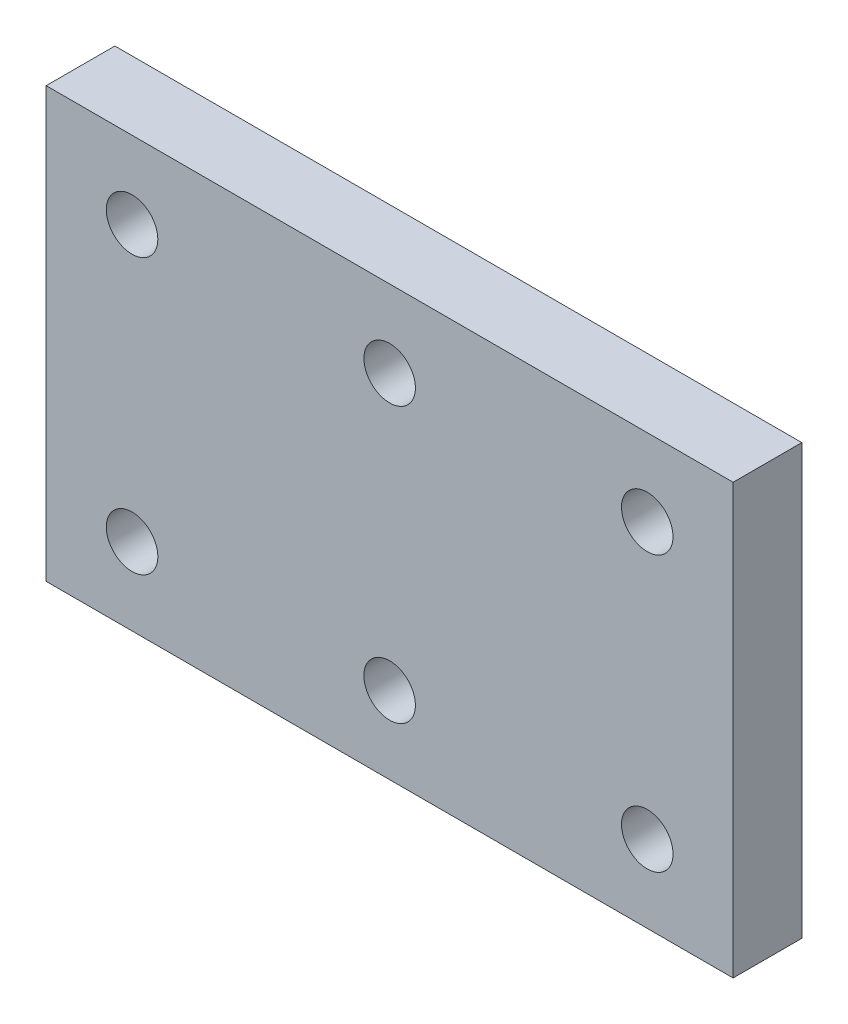
SolidWorks part; units mm, degrees
ref_plane "前视基准面" through (0, 0, 0) normal (0, 0, 1) x (1, 0, 0)
ref_plane "上视基准面" through (0, 0, 0) normal (0, 1, 0) x (1, 0, 0)
ref_plane "右视基准面" through (0, 0, 0) normal (1, 0, 0) x (0, 0, -1)
sketch "草图2" plane through (0, 0, 0) normal (0, 0, 1) x (1, 0, 0)
  line L1 (-20, -12.5) -> (20, -12.5)
  line L2 (-20, -12.5) -> (-20, 12.5)
  line L3 (-20, 12.5) -> (20, 12.5)
  line L4 (20, -12.5) -> (20, 12.5)
  line L5 (-20, -12.5) -> (20, 12.5) construction
  line L6 (-20, 12.5) -> (20, -12.5) construction
  point P0 (0, 0)
  dimension "D1" = 25
  dimension "D2" = 40
extrude "凸台-拉伸1" add sketch "草图2" along normal blind 4
sketch "草图3" plane through (0, 0, 4) normal (0, 0, 1) x (1, 0, 0)
  line L0 (0, 0) -> (50000, 0) construction
  line L1 (0, 0) -> (0, 50000) construction
  circle A0 centre (-15, 8) radius 1.5
  circle A1 centre (0, 8) radius 1.5
  circle A2 centre (15, 8) radius 1.5
  circle A5 centre (15, -8) radius 1.5
  circle A6 centre (0, -8) radius 1.5
  circle A7 centre (-15, -8) radius 1.5
  dimension "D1" = 3
  dimension "3" = 3
  dimension "D2" = 30
  dimension "D3" = 15
  dimension "D4" = 16
extrude "切除-拉伸1" cut sketch "草图3" against normal blind 4
